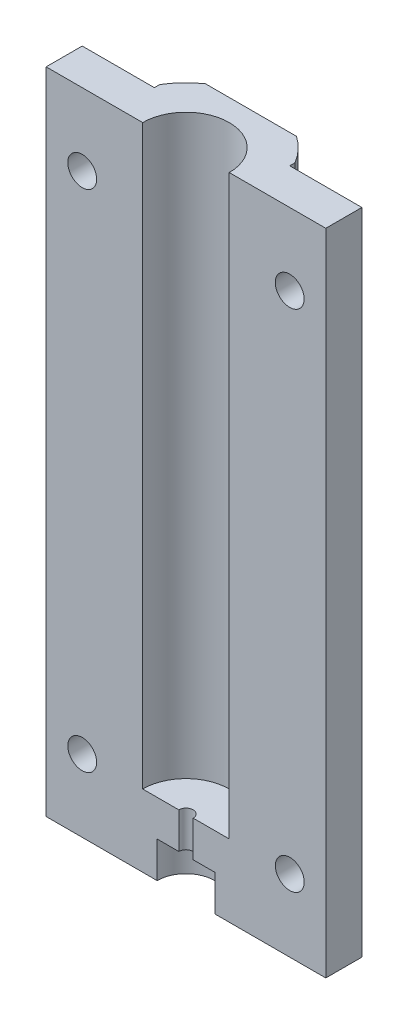
SolidWorks part; units mm, degrees
ref_plane "Ebene vorne" through (0, 0, 0) normal (0, 0, 1) x (1, 0, 0)
ref_plane "Ebene oben" through (0, 0, 0) normal (0, 1, 0) x (1, 0, 0)
ref_plane "Ebene rechts" through (0, 0, 0) normal (1, 0, 0) x (0, 0, -1)
sketch "Skizze3" plane through (0, 0, 0) normal (0, 0, 1) x (1, 0, 0)
  line L0 (0, 0) -> (-11, 0)
  line L1 (-11, 0) -> (-11, 90)
  line L2 (-11, 90) -> (-6, 90)
  line L3 (-6, 90) -> (-6, 10)
  line L4 (-6, 10) -> (0, 10)
  line L5 (0, 10) -> (0, 0)
  line L6 (0, 0) -> (0, 91.7062) construction
  dimension "D1" = 90
  dimension "D2" = 11
  dimension "D3" = 80
  dimension "D4" = 5
revolve "Rotation1" add sketch "Skizze3" angle 180 about L6
sketch "Skizze6" plane through (0, 90, 0) normal (0, 1, 0) x (1, 0, 0)
  line L0 (-9.3806, -5.7449) -> (-9.3806, 0)
  line L1 (-6, 0) -> (-11, 0) construction
  arc A0 (-11, 0) -> (11, 0) centre (0, 0) ccw construction
extrude "Schnitt-Linear austragen2" cut sketch "Skizze6" against normal blind 90 and the other way through all
sketch "Skizze7" plane through (0, 0, 0) normal (0, -1, 0) x (1, 0, 0)
  line L1 (9.3806, 5.7449) -> (9.3806, 0)
  line L2 (11, 0) -> (-9.3806, 0) construction
  arc A0 (11, 0) -> (-9.3806, 5.7449) centre (0, 0) ccw construction
extrude "Schnitt-Linear austragen3" cut sketch "Skizze7" against normal blind 90 and the other way through all
sketch "Skizze8" plane through (0, 90, 0) normal (0, 1, 0) x (1, 0, 0)
  line L1 (-9.3806, 0) -> (-19.3806, 0)
  line L2 (-9.3806, 0) -> (-9.3806, -5)
  line L3 (-9.3806, -5) -> (-19.3806, -5)
  line L4 (-19.3806, 0) -> (-19.3806, -5)
  dimension "D1" = 10
  dimension "D2" = 5
extrude "Aufsatz-Linear austragen2" add sketch "Skizze8" against normal blind 90
sketch "Skizze9" plane through (0, 90, 0) normal (0, 1, 0) x (1, 0, 0)
  line L1 (9.3806, 0) -> (19.3806, 0)
  line L2 (9.3806, 0) -> (9.3806, -5)
  line L3 (9.3806, -5) -> (19.3806, -5)
  line L4 (19.3806, 0) -> (19.3806, -5)
  dimension "D1" = 10
  dimension "D2" = 5
extrude "Aufsatz-Linear austragen3" add sketch "Skizze9" against normal blind 90
sketch "Skizze12" plane through (0, 0, 0) normal (0, -1, 0) x (-1, 0, 0)
  line L0 (0, 0) -> (0, -26.0405) construction
  circle A0 centre (0, 0) radius 1
  dimension "D1" = 2
extrude "Schnitt-Linear austragen5" cut sketch "Skizze12" against normal blind 20
mirror "Spiegeln2" of bodies 110
sketch "Skizze13" plane through (0, 0, 0) normal (0, -1, 0) x (-1, 0, 0)
  line L1 (0, 0) -> (-19.3806, 0) construction
  line L2 (-19.3806, -5) -> (-19.3806, 5) construction
  line L3 (-19.3806, 0) -> (19.3806, 0) construction
  line L4 (19.3806, 5) -> (19.3806, -5) construction
  line L5 (19.3806, 0) -> (-19.3806, 0)
  line L6 (19.3806, 0) -> (19.3806, -19.7242)
  line L7 (19.3806, -19.7242) -> (-19.3806, -19.7242)
  line L8 (-19.3806, 0) -> (-19.3806, -19.7242)
extrude "Schnitt-Linear austragen7" cut sketch "Skizze13" against normal blind 90
sketch "Skizze14" plane through (0, 0, 0) normal (0, -1, 0) x (-1, 0, 0)
  circle A0 centre (0, 0) radius 4
  dimension "D1" = 8
extrude "Schnitt-Linear austragen8" cut sketch "Skizze14" against normal blind 5
sketch "Skizze15" plane through (0, 0, -5) normal (0, 0, -1) x (-1, 0, 0)
  line L0 (-9.3806, 90) -> (-19.3806, 90) construction
  line L1 (-19.3806, 0) -> (-19.3806, 90) construction
  line L2 (-9.3806, 0) -> (-19.3806, 0) construction
  line L3 (19.3806, 0) -> (9.3806, 0) construction
  line L4 (19.3806, 90) -> (9.3806, 90) construction
  line L5 (19.3806, 0) -> (19.3806, 90) construction
  circle A0 centre (-14.3806, 80) radius 2
  circle A1 centre (-14.393, 10) radius 2
  circle A2 centre (14.3806, 10) radius 2
  circle A3 centre (14.3806, 80) radius 2
  dimension "D1" = 4
  dimension "D2" = 4
  dimension "D3" = 4
  dimension "D4" = 4
  dimension "D5" = 10
  dimension "D6" = 5
  dimension "D7" = 10
  dimension "D8" = 10
  dimension "D9" = 10
  dimension "D10" = 5
  dimension "D11" = 5
extrude "Schnitt-Linear austragen9" cut sketch "Skizze15" against normal through all
sketch "Skizze17" plane through (0, 90, 0) normal (0, 1, 0) x (1, 0, 0)
  line L0 (0, 0) -> (0, 11) construction
  line L2 (-10.4548, 11.0093) -> (11.0025, 11.0093)
  line L3 (-10.4548, 11.0093) -> (-10.4548, 9.0093)
  line L4 (-10.4548, 9.0093) -> (11.0025, 9.0093)
  line L5 (11.0025, 11.0093) -> (11.0025, 9.0093)
  arc A0 (9.3806, 5.7449) -> (-9.3806, 5.7449) centre (0, 0) ccw construction
  dimension "D1" = 11
  dimension "D2" = 2
extrude "Schnitt-Linear austragen16" cut sketch "Skizze17" against normal through all
